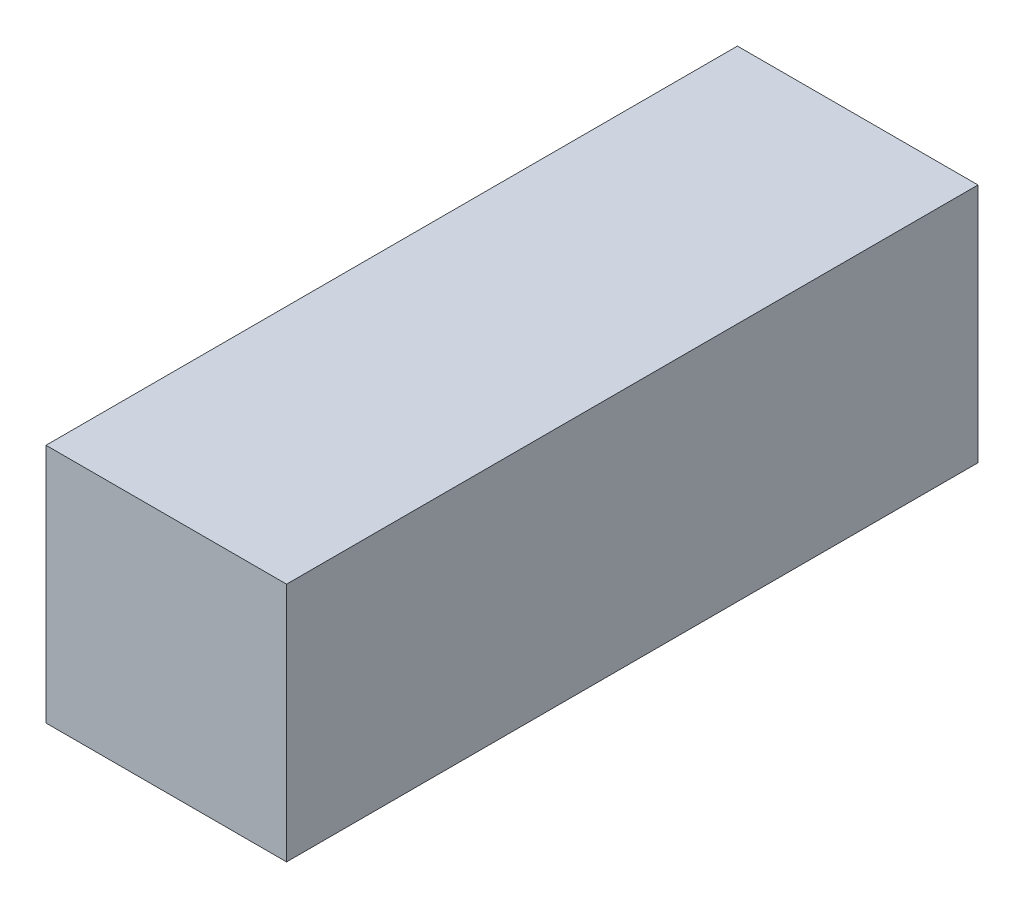
SolidWorks part; units mm, degrees
ref_plane "Front Plane" through (0, 0, 0) normal (0, 0, 1) x (1, 0, 0)
ref_plane "Top Plane" through (0, 0, 0) normal (0, 1, 0) x (1, 0, 0)
ref_plane "Right Plane" through (0, 0, 0) normal (1, 0, 0) x (0, 0, -1)
sketch "Sketch1" plane through (0, 0, 0) normal (0, 0, 1) x (1, 0, 0)
  line L1 (-3.175, -3.175) -> (3.175, -3.175)
  line L2 (-3.175, -3.175) -> (-3.175, 3.175)
  line L3 (-3.175, 3.175) -> (3.175, 3.175)
  line L4 (3.175, -3.175) -> (3.175, 3.175)
  line L5 (-3.175, -3.175) -> (3.175, 3.175) construction
  line L6 (-3.175, 3.175) -> (3.175, -3.175) construction
  point P0 (0, 0)
  dimension "D1" = 6.35
extrude "Boss-Extrude1" add sketch "Sketch1" along normal blind 18.25
